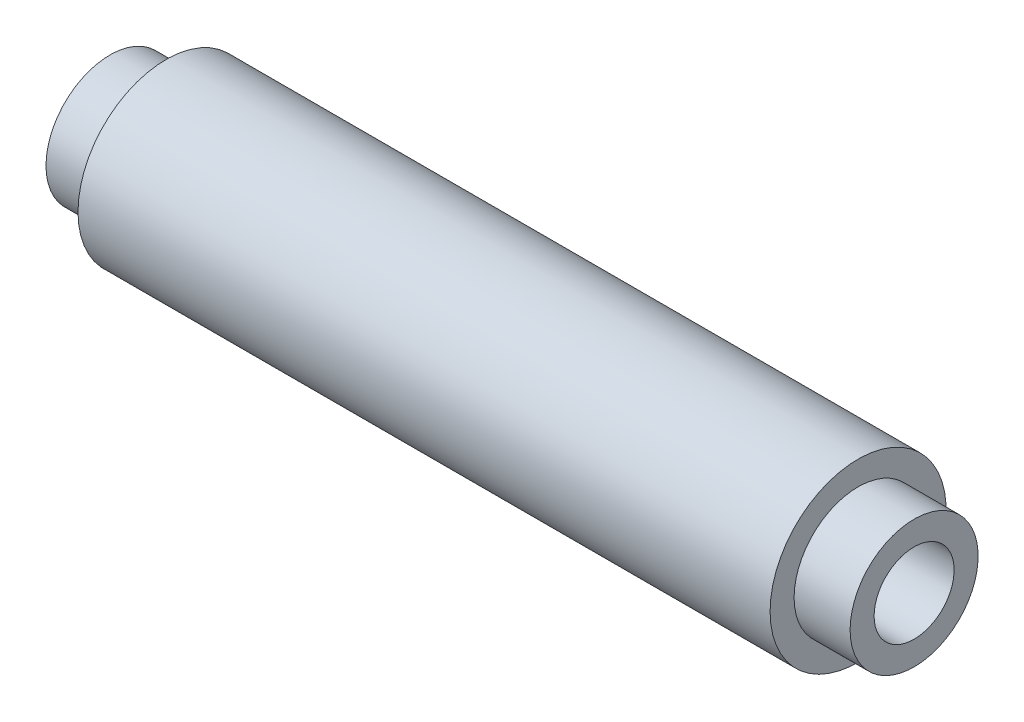
SolidWorks part; units mm, degrees
ref_plane "Front Plane" through (0, 0, 0) normal (0, 0, 1) x (1, 0, 0)
ref_plane "Top Plane" through (0, 0, 0) normal (0, 1, 0) x (1, 0, 0)
ref_plane "Right Plane" through (0, 0, 0) normal (1, 0, 0) x (0, 0, -1)
sketch "Sketch1" plane through (0, 0, 0) normal (0, 0, 1) x (1, 0, 0)
  line L0 (0, 0) -> (73.2003, 0) construction
  line L1 (0, 2.5) -> (12.5, 2.5)
  line L2 (50.25, 2.5) -> (50.25, 4)
  line L3 (50.25, 4) -> (46.75, 4)
  line L4 (46.75, 4) -> (46.75, 5.5)
  line L5 (46.75, 5.5) -> (3.5, 5.5)
  line L6 (3.5, 5.5) -> (3.5, 4)
  line L7 (3.5, 4) -> (0, 4)
  line L8 (0, 4) -> (0, 2.5)
  line L9 (37.75, 2.5) -> (37.75, 0)
  line L10 (37.75, 0) -> (12.5, 0)
  line L11 (12.5, 0) -> (12.5, 2.5)
  line L12 (37.75, 2.5) -> (50.25, 2.5)
  point P10 (3.5, 4.75)
  dimension "D1" = 43.25
  dimension "D2" = 1.5
  dimension "D3" = 3.5
  dimension "D4" = 12.5
  dimension "D5" = 1.5
  dimension "D6" = 2.5
revolve "Revolve1" add sketch "Sketch1" angle 360 about L0
